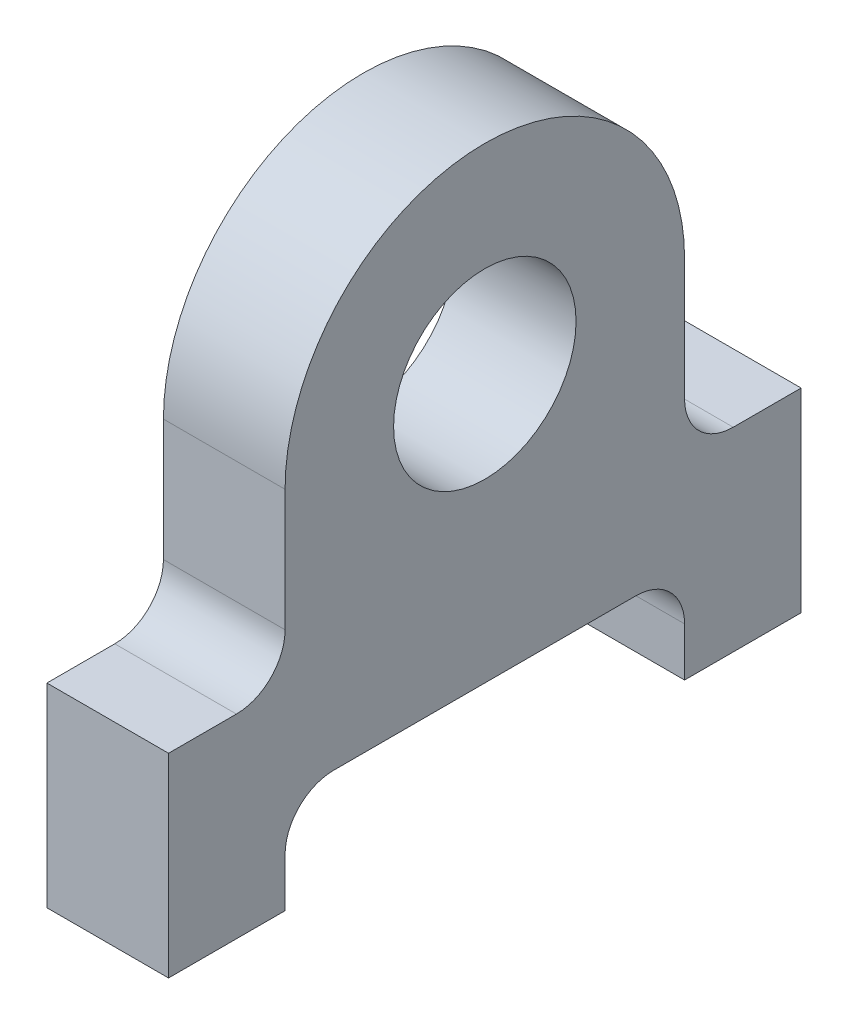
SolidWorks part; units mm, degrees
ref_plane "Front Plane" through (0, 0, 0) normal (0, 0, 1) x (1, 0, 0)
ref_plane "Top Plane" through (0, 0, 0) normal (0, 1, 0) x (1, 0, 0)
ref_plane "Right Plane" through (0, 0, 0) normal (1, 0, 0) x (0, 0, -1)
sketch "Sketch1" plane through (0, 0, 0) normal (1, 0, 0) x (0, 0, -1)
  line L0 (-16.51, -19.05) -> (-10.4267, -19.05)
  line L1 (-10.4267, -19.05) -> (-10.4267, -16.51)
  line L2 (-7.8867, -13.97) -> (7.8867, -13.97)
  line L5 (-10.4267, 0) -> (-10.4267, -6.35)
  line L6 (-16.51, -8.89) -> (-16.51, -19.05)
  line L7 (0, 10.4267) -> (0, -13.97) construction
  line L8 (-12.9667, -8.89) -> (-16.51, -8.89)
  line L9 (12.9667, -8.89) -> (16.51, -8.89)
  line L10 (16.51, -8.89) -> (16.51, -19.05)
  line L11 (10.4267, 0) -> (10.4267, -6.35)
  line L12 (10.4267, -19.05) -> (10.4267, -16.51)
  line L13 (16.51, -19.05) -> (10.4267, -19.05)
  arc A0 (-10.4267, -16.51) -> (-7.8867, -13.97) centre (-7.8867, -16.51) cw
  circle A1 centre (0, 0) radius 4.7625
  arc A2 (10.4267, 0) -> (-10.4267, 0) centre (0, 0) ccw
  arc A4 (-10.4267, -6.35) -> (-12.9667, -8.89) centre (-12.9667, -6.35) cw
  arc A5 (10.4267, -6.35) -> (12.9667, -8.89) centre (12.9667, -6.35) ccw
  arc A6 (10.4267, -16.51) -> (7.8867, -13.97) centre (7.8867, -16.51) ccw
  point P13 (1.4188, -1.2111)
  point P16 (0, 0)
  point P18 (-0.3677, -5.0174)
  point P19 (-0.8434, 1.4706)
  point P20 (-12.9112, -10.0348)
  point P21 (1.4188, -2.1627)
  point P22 (0, 0)
  point P23 (0, 0)
  point P24 (1.4188, -1.2544)
  point P25 (0, 0)
  point P26 (0, 0)
  point P27 (0, 0)
  point P28 (0, 0)
  point P29 (0, 0)
  point P30 (0, 0)
  point P31 (0, 0)
  point P41 (0, 10.4267)
  dimension "D6" = 4.7625
  dimension "D7" = 2.54
  dimension "D1" = 10.16
  dimension "D2" = 19.05
  dimension "D3" = 5.08
  dimension "D4" = 33.02
  dimension "D5" = 20.8534
extrude "Boss-Extrude1" add sketch "Sketch1" along normal blind 6.35
